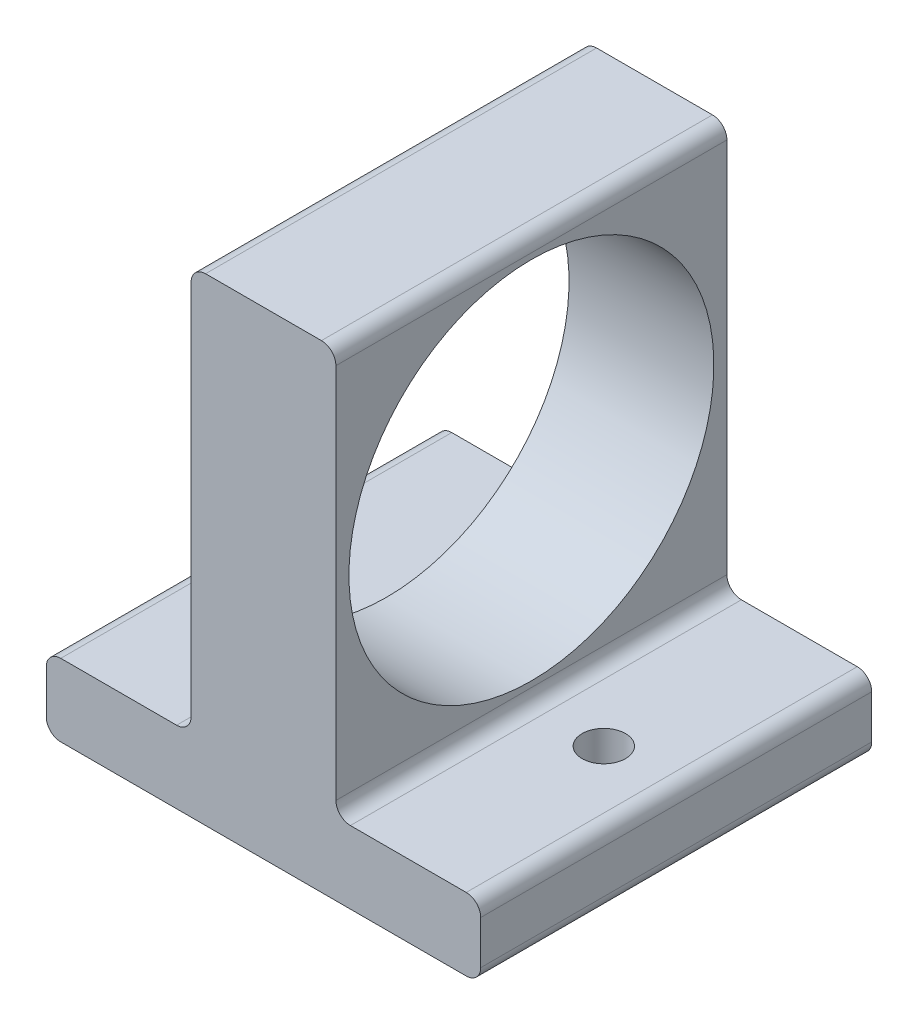
SolidWorks part; units mm, degrees
ref_plane "Front Plane" through (0, 0, 0) normal (0, 0, 1) x (1, 0, 0)
ref_plane "Top Plane" through (0, 0, 0) normal (0, 1, 0) x (1, 0, 0)
ref_plane "Right Plane" through (0, 0, 0) normal (1, 0, 0) x (0, 0, -1)
sketch "Sketch1" plane through (0, 0, 0) normal (0, 0, 1) x (1, 0, 0)
  line L0 (-14, 0) -> (-6, 0)
  line L1 (-5, 1) -> (-5, 27)
  line L2 (0, 28) -> (0, -31.4693) construction
  line L3 (-4, 28) -> (4, 28)
  line L4 (-15, -1) -> (-15, -4)
  line L5 (-14, -5) -> (14, -5)
  line L6 (15, -1) -> (15, -4)
  line L7 (14, 0) -> (6, 0)
  line L8 (5, 1) -> (5, 27)
  arc A0 (-5, 27) -> (-4, 28) centre (-4, 27) cw
  arc A1 (-14, -5) -> (-15, -4) centre (-14, -4) cw
  arc A2 (-15, -1) -> (-14, 0) centre (-14, -1) cw
  arc A3 (-6, 0) -> (-5, 1) centre (-6, 1) ccw
  arc A4 (14, -5) -> (15, -4) centre (14, -4) ccw
  arc A5 (15, -1) -> (14, 0) centre (14, -1) ccw
  arc A6 (6, 0) -> (5, 1) centre (6, 1) cw
  arc A7 (5, 27) -> (4, 28) centre (4, 27) ccw
  point P10 (-5, 28)
  point P15 (-15, 0)
  point P18 (-5, 0)
  point P20 (0, -5)
  dimension "D5" = 1
  dimension "D6" = 1
  dimension "D1" = 10
  dimension "D2" = 28
  dimension "D3" = 5
  dimension "D4" = 5
extrude "Boss-Extrude1" add sketch "Sketch1" along normal blind 27
sketch "Sketch2" plane through (5, 0, 0) normal (1, 0, 0) x (0, 0, -1)
  line L0 (-27, 27) -> (0, 1) construction
  line L1 (-27, 1) -> (0, 1)
  line L2 (-27, 1) -> (-27, 27)
  line L3 (-27, 27) -> (0, 27)
  line L4 (0, 1) -> (0, 27)
  line L5 (0, 27) -> (-27, 1)
  circle A1 centre (-13.5, 14) radius 12.6
extrude "Cut-Extrude1" cut sketch "Sketch2" against normal up to next contours A1
sketch "Sketch3" plane through (0, -5, 0) normal (0, -1, 0) x (1, 0, 0)
  line L0 (0, 27) -> (0, -3.3613) construction
  line L1 (-14, 27) -> (14, 27) construction
  line L2 (-14, 13.5) -> (14, 13.5) construction
  line L3 (-14, 27) -> (-14, 0) construction
  line L4 (14, 27) -> (14, 0) construction
  circle A0 centre (-10, 13.5) radius 1.5
  circle A1 centre (10, 13.5) radius 1.5
  dimension "D1" = 10
extrude "Cut-Extrude2" cut sketch "Sketch3" against normal up to next
